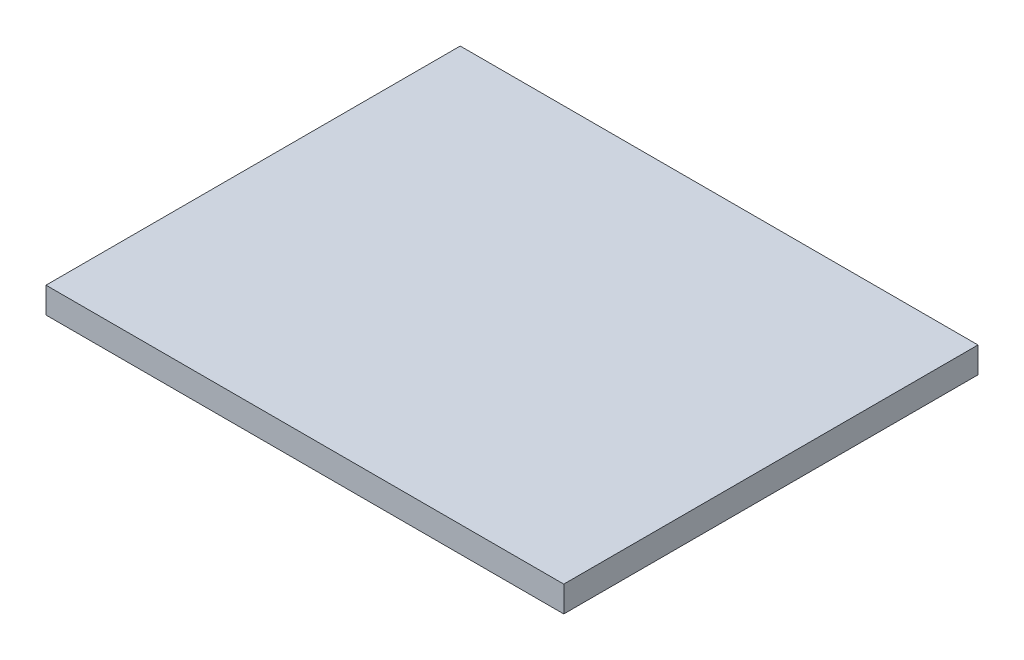
SolidWorks part; units mm, degrees
ref_plane "Front Plane" through (0, 0, 0) normal (0, 0, 1) x (1, 0, 0)
ref_plane "Top Plane" through (0, 0, 0) normal (0, 1, 0) x (1, 0, 0)
ref_plane "Right Plane" through (0, 0, 0) normal (1, 0, 0) x (0, 0, -1)
sketch "Sketch1" plane through (0, 0, 0) normal (0, 1, 0) x (1, 0, 0)
  line L1 (1, 0.8) -> (-1, 0.8)
  line L2 (1, 0.8) -> (1, -0.8)
  line L3 (1, -0.8) -> (-1, -0.8)
  line L4 (-1, 0.8) -> (-1, -0.8)
  line L5 (1, 0.8) -> (-1, -0.8) construction
  line L6 (1, -0.8) -> (-1, 0.8) construction
  point P0 (0, 0)
  dimension "D1" = 2
  dimension "D2" = 1.6
extrude "Boss-Extrude1" add sketch "Sketch1" along normal blind 0.1
